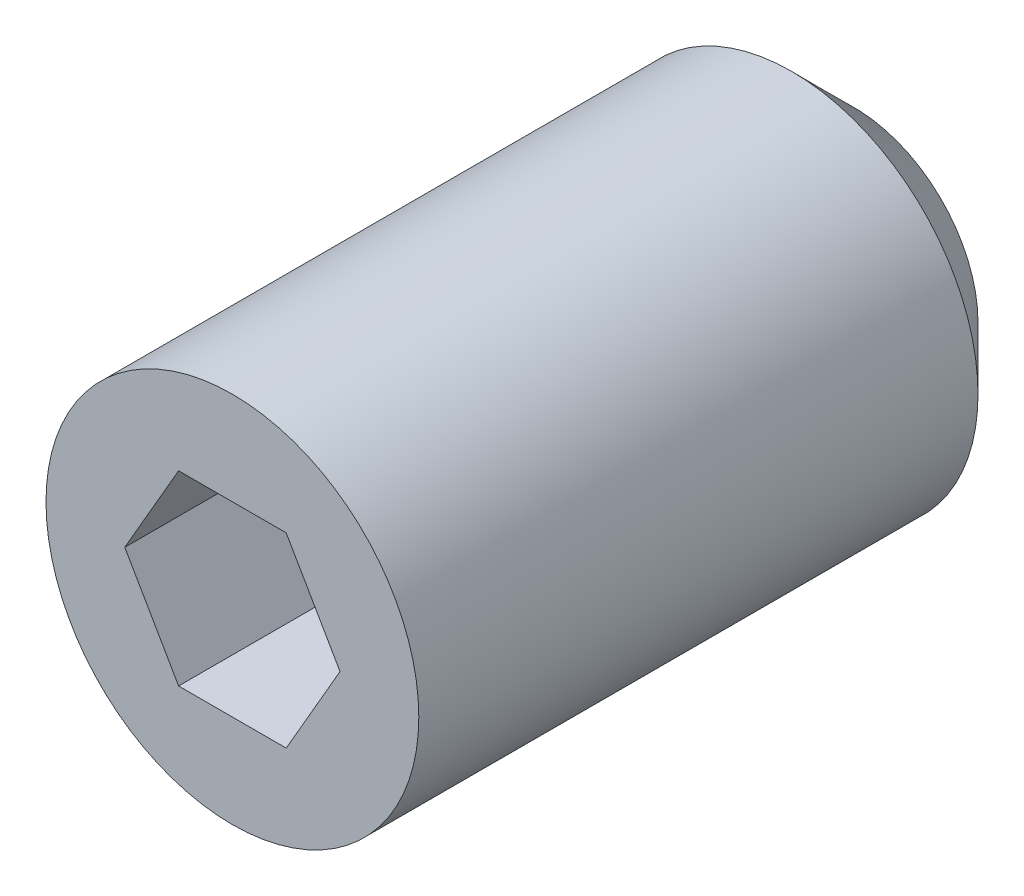
SolidWorks part; units mm, degrees
ref_plane "Front Plane" through (0, 0, 0) normal (0, 0, 1) x (1, 0, 0)
ref_plane "Top Plane" through (0, 0, 0) normal (0, 1, 0) x (1, 0, 0)
ref_plane "Right Plane" through (0, 0, 0) normal (1, 0, 0) x (0, 0, -1)
sketch "Sketch1" plane through (0, 0, 0) normal (0, 0, 1) x (1, 0, 0)
  circle A0 centre (0, 0) radius 1.5
  dimension "D1" = 3
extrude "Boss-Extrude1" add sketch "Sketch1" against normal blind 5
sketch "Sketch2" plane through (0, 0, 0) normal (0, 0, 1) x (1, 0, 0)
  line L1 (0.866, 0) -> (0.433, 0.75)
  line L2 (0.433, 0.75) -> (-0.433, 0.75)
  line L3 (-0.433, 0.75) -> (-0.866, 0)
  line L4 (-0.866, 0) -> (-0.433, -0.75)
  line L5 (-0.433, -0.75) -> (0.433, -0.75)
  line L6 (0.433, -0.75) -> (0.866, 0)
  circle A0 centre (0, 0) radius 0.75 construction
  dimension "D1" = 1.5
extrude "Cut-Extrude1" cut sketch "Sketch2" against normal blind 1.2
sketch3d "3DSketch1"
  line L0 (0, 0, 0) -> (0, 0, -5) construction
sketch "Sketch3" plane through (0, 0, 0) normal (1, 0, 0) x (0, 0, -1)
  line L0 (5, 1.5) -> (5, -1.5)
  line L1 (5, 1.5) -> (5, 1)
  line L2 (0, 0) -> (5, 0) construction
  line L3 (5, 1) -> (4.5, 1.5)
  line L5 (5, 1.5) -> (0, 1.5)
  line L6 (0, -0.8) -> (5, -1.5)
  line L8 (5, 1.5) -> (4.5, 1.5)
  dimension "D1" = 1
  dimension "D3" = 45
revolve "Chamfer" cut sketch "Sketch3" angle 360 about L0
sketch "Sketch4" plane through (0, 0, 0) normal (1, 0, 0) x (0, 0, -1)
  line L0 (5, 1) -> (5, -1)
  line L1 (5, 1) -> (5, 0)
  line L2 (5, 0) -> (4.636, 0)
  line L3 (4.636, 0) -> (5, 1)
  dimension "D1" = 20
revolve "Hollow" [suppressed] cut sketch "Sketch4" angle 360 about L2
sketch "Sketch5" plane through (0, 0, 0) normal (1, 0, 0) x (0, 0, -1)
  line L0 (0, 0) -> (5, 0) construction
  line L1 (4.5, 0) -> (5, 0) construction
  line L2 (4.5, 1.5) -> (4.5, 0) construction
  line L3 (5, 1) -> (5, -1)
  line L4 (5, 0) -> (5, -1) construction
  line L5 (4.5, 1.5) -> (5.25, 1.5)
  line L6 (5.25, 1.5) -> (5.25, 0)
  line L7 (5.25, 0) -> (5, 0)
  line L9 (4.5, 1.5) -> (0, 1.5)
  line L13 (0, -0.8) -> (1.8, -0.8)
  line L15 (-1, 1.5) -> (0, 1.5) construction
  arc A0 (4.5, 1.5) -> (5, 0) centre (2.5, 0) cw
  dimension "D1" = 0.25
  dimension "D2" = 1
revolve "Domed" [suppressed] cut sketch "Sketch5" angle 360 about L7
sketch "Sketch6" plane through (0, 0, 0) normal (1, 0, 0) x (0, 0, -1)
  line L0 (5, 1) -> (5, -1)
  line L1 (5, 1) -> (5, 0) construction
  line L3 (4.5, 1.5) -> (4, 1.5)
  line L6 (4.5, 1.5) -> (0, 1.5)
  line L7 (5, 1) -> (4.5, 1.5)
  line L8 (4.5, 1.5) -> (0, 1.5) construction
  line L9 (4, 1.5) -> (4.5, 1)
  line L10 (4.5, 1) -> (5, 1)
  line L11 (0, -0.8) -> (1.8, -0.8)
  line L12 (0, 1.5) -> (0, -1.5) construction
  line L13 (0, 1.5) -> (-1, 1.5) construction
  dimension "D1" = 0.5
  dimension "D2" = 1
revolve "Dog" [suppressed] cut sketch "Sketch6" angle 360
